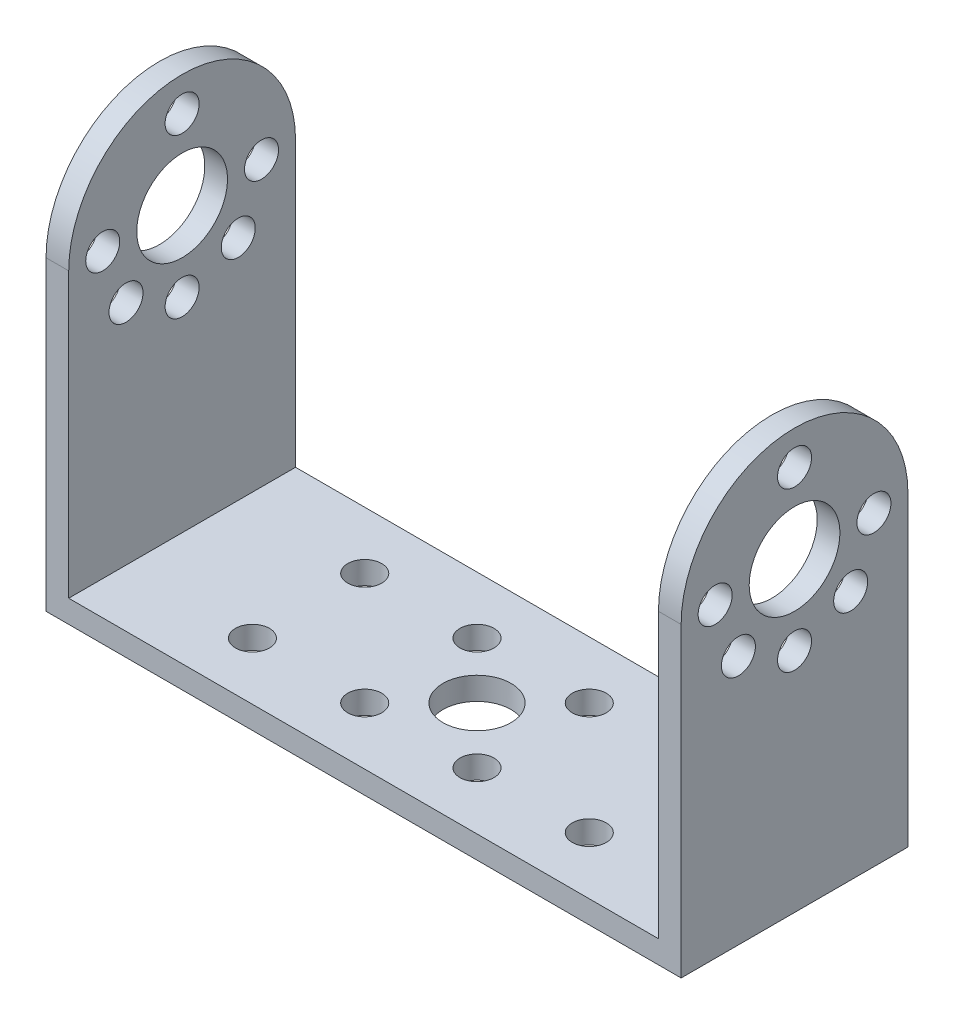
SolidWorks part; units mm, degrees
ref_plane "前视基准面" through (0, 0, 0) normal (0, 0, 1) x (1, 0, 0)
ref_plane "上视基准面" through (0, 0, 0) normal (0, 1, 0) x (1, 0, 0)
ref_plane "右视基准面" through (0, 0, 0) normal (1, 0, 0) x (0, 0, -1)
sketch "草图1" plane through (0, 0, 0) normal (0, 1, 0) x (1, 0, 0)
  line L1 (0, 0) -> (56, 0)
  line L2 (0, 0) -> (0, 20)
  line L3 (0, 20) -> (56, 20)
  line L4 (56, 0) -> (56, 20)
  dimension "D1" = 20
  dimension "D2" = 56
extrude "凸台-拉伸1" add sketch "草图1" along normal blind 2
sketch "草图2" plane through (0, 2, 0) normal (0, 1, 0) x (1, 0, 0)
  line L0 (28, 20) -> (28, 0) construction
  line L1 (56, 20) -> (0, 20) construction
  line L2 (0, 10) -> (56, 10) construction
  line L3 (0, 20) -> (0, 0) construction
  line L4 (56, 0) -> (56, 20) construction
  line L5 (28, 10) -> (35.7612, 2.2388) construction
  line L6 (23.0503, 14.9497) -> (23.0503, 5.0503) construction
  line L7 (18.1005, 10) -> (25.8617, 2.2388) construction
  circle A0 centre (28, 10) radius 3
  circle A1 centre (28, 10) radius 7 construction
  circle A2 centre (32.9497, 5.0503) radius 1.5
  circle A3 centre (23.0503, 5.0503) radius 1.5
  circle A4 centre (23.0503, 14.9497) radius 1.5
  circle A5 centre (32.9497, 14.9497) radius 1.5
  circle A6 centre (18.1005, 10) radius 7 construction
  circle A7 centre (13.1508, 14.9497) radius 1.5
  circle A8 centre (13.1508, 5.0503) radius 1.5
  circle A9 centre (42.8492, 5.0503) radius 1.5
  circle A10 centre (42.8492, 14.9497) radius 1.5
  point P26 (28, 10)
  dimension "D1" = 4
extrude "切除-拉伸1" cut sketch "草图2" against normal up to next
sketch "草图3" plane through (0, 0, 0) normal (-1, 0, 0) x (0, 0, 1)
  line L1 (-20, 2) -> (0, 2)
  line L2 (-20, 2) -> (-20, 27)
  line L4 (0, 2) -> (0, 27)
  arc A0 (0, 27) -> (-20, 27) centre (-10, 27) ccw
  dimension "D5" = 10
  dimension "D1" = 25
  dimension "D2" = 20
  dimension "D3" = 25
  dimension "D4" = 25
extrude "凸台-拉伸2" add sketch "草图3" against normal blind 2
sketch "草图4" plane through (0, 0, 0) normal (-1, 0, 0) x (0, 0, 1)
  circle A0 centre (-10, 27) radius 4
  circle A1 centre (-10, 27) radius 7 construction
  circle A2 centre (-10, 34) radius 1.5
  circle A3 centre (-5.0503, 31.9497) radius 1.5 [skipped]
  circle A4 centre (-3, 27) radius 1.5
  circle A5 centre (-5.0503, 22.0503) radius 1.5
  circle A6 centre (-10, 20) radius 1.5
  circle A7 centre (-14.9497, 22.0503) radius 1.5
  circle A8 centre (-17, 27) radius 1.5
  circle A9 centre (-14.9497, 31.9497) radius 1.5 [skipped]
  point P23 (-10, 27)
  dimension "D1" = 8
  dimension "D2" = 14
extrude "切除-拉伸2" cut sketch "草图4" against normal up to next
ref_plane "基准面1" through (28, 0, 0) normal (-1, 0, 0) x (0, 0, 1)
mirror "镜向1" about plane through (28, 0, 0) normal (-1, 0, 0) of "凸台-拉伸2", "切除-拉伸2"
ref_plane "基准面2" through (0, 0, -10) normal (0, 0, 1) x (1, 0, 0)
ref_plane "基准面3" through (0, 0, -10) normal (0, 0, 1) x (1, 0, 0)
